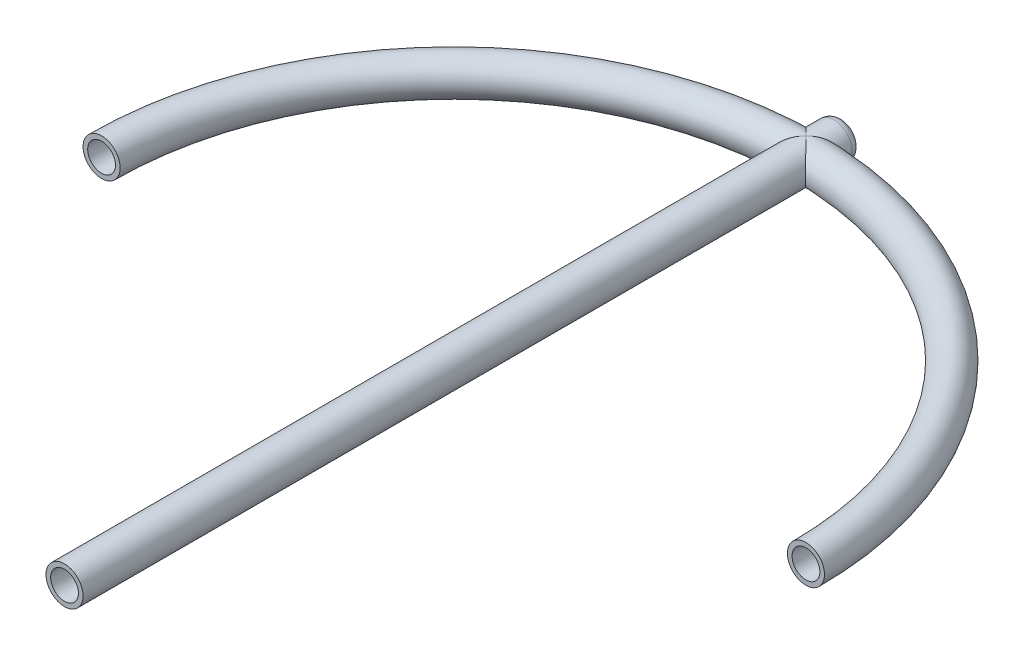
SolidWorks part; units mm, degrees
ref_plane "Front Plane" through (0, 0, 0) normal (0, 0, 1) x (1, 0, 0)
ref_plane "Top Plane" through (0, 0, 0) normal (0, 1, 0) x (1, 0, 0)
ref_plane "Right Plane" through (0, 0, 0) normal (1, 0, 0) x (0, 0, -1)
sketch "Sketch1" plane through (0, 0, 0) normal (0, 0, 1) x (1, 0, 0)
  circle A0 centre (-19, 0) radius 0.75
  circle A1 centre (-19, 0) radius 1
  circle A2 centre (19, 0) radius 0.75
  circle A3 centre (19, 0) radius 1
  point P6 (0, 0)
  point P8 (0, 0)
  point P9 (0.8933, -0.3289)
  dimension "D1" = 19
  dimension "D3" = 2
  dimension "D4" = 1.5
  dimension "D5" = 2
  dimension "D6" = 1.5
  dimension "D2" = 19
sketch "Sketch4" plane through (0, 0, 0) normal (0, 1, 0) x (1, 0, 0)
  line L2 (-20, 0) -> (-18, 0) construction
  line L3 (18.25, 0) -> (19.75, 0) construction
  arc A0 (-19, 0) -> (19, 0) centre (0, 0) cw
sweep "Sweep2" add profiles "Sketch1" path "Sketch4"
sketch "Sketch8" plane through (0, 0, 0) normal (1, 0, 0) x (0, 0, -1)
  line L1 (0, -1) -> (-20.4596, -1)
  line L2 (0, -1) -> (0, 1.066)
  line L3 (0, 1.066) -> (-20.4596, 1.066)
  line L4 (-20.4596, -1) -> (-20.4596, 1.066)
extrude "Cut-Extrude1" cut sketch "Sketch8" against normal through all both and the other way through all
sketch "Sketch9" plane through (0, 0, 0) normal (0, 0, 1) x (1, 0, 0)
  circle A0 centre (0, 0) radius 0.75
  circle A1 centre (0, 0) radius 1
  dimension "D1" = 1.5
  dimension "D2" = 2
extrude "Boss-Extrude1" add sketch "Sketch9" against normal blind 21 and the other way blind 21
sketch "Sketch10" plane through (0, 0, -21) normal (0, 0, -1) x (-1, 0, 0)
  circle A0 centre (0, 0) radius 0.75
extrude "Boss-Extrude4" add sketch "Sketch10" against normal blind 2
fillet "Fillet3" radius 0.5 1 edges at (1, 0, -21)
equation "\".5.00mm\"=1"
